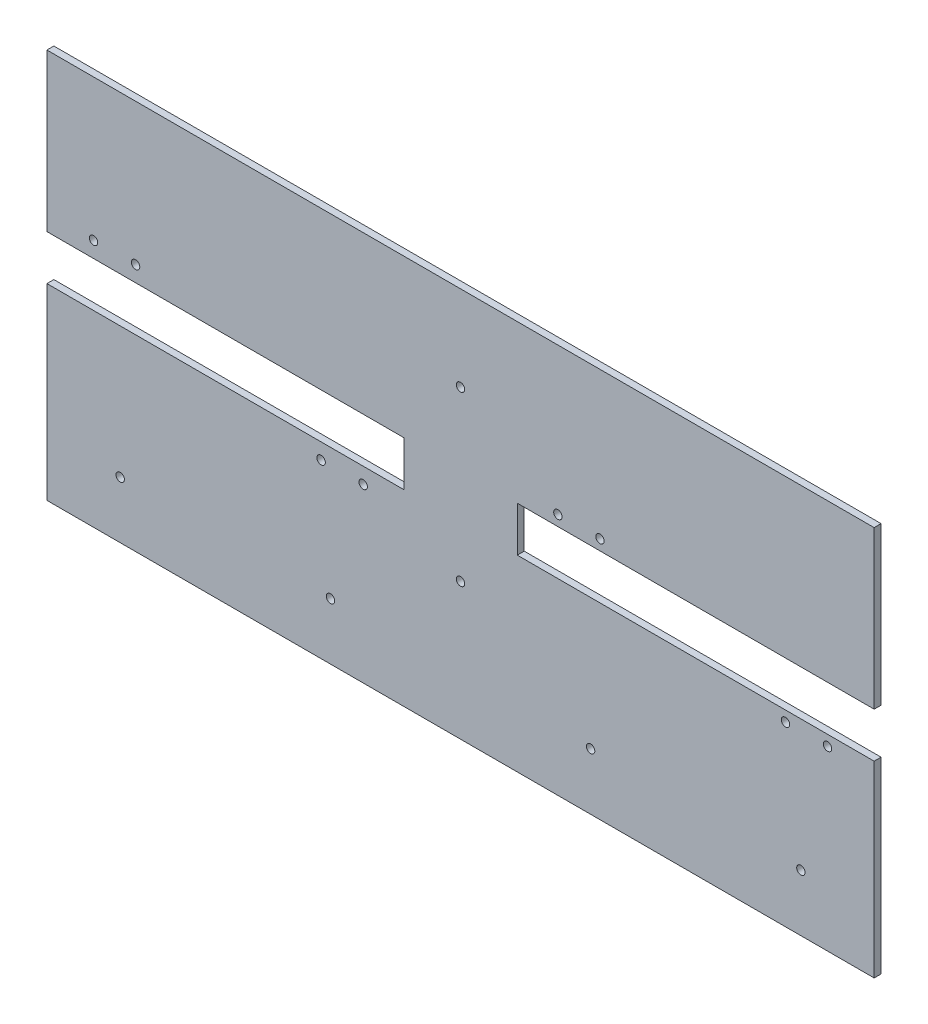
SolidWorks part; units mm, degrees
material "Balsa"
ref_plane "Front Plane" through (0, 0, 0) normal (0, 0, 1) x (1, 0, 0)
ref_plane "Top Plane" through (0, 0, 0) normal (0, 1, 0) x (1, 0, 0)
ref_plane "Right Plane" through (0, 0, 0) normal (1, 0, 0) x (0, 0, -1)
sketch "Sketch1" plane through (0, 0, 0) normal (0, 0, 1) x (1, 0, 0)
  line L0 (223.7, 160.9919) -> (54, 160.9919) construction
  line L1 (223.7, -24.5) -> (-169.7, -24.5)
  line L2 (223.7, -24.5) -> (223.7, 160.9919)
  line L3 (223.7, 160.9919) -> (-169.7, 160.9919)
  line L4 (-169.7, -24.5) -> (-169.7, 160.9919)
  line L5 (223.7, -24.5) -> (-169.7, 160.9919) construction
  line L6 (223.7, 160.9919) -> (-169.7, -24.5) construction
  line L7 (227, -24.5) -> (223.7, -24.5) construction
  line L10 (223.7, 144.1231) -> (223.7, -24.5) construction
  line L11 (-169.7, -24.5) -> (-169.7, 144.1269) construction
  point P4 (27, 68.246)
extrude "Boss-Extrude1" add sketch "Sketch1" along normal up to surface (3.3 mm away)
sketch "Sketch2" plane through (0, 0, 0) normal (0, 0, -1) x (-1, 0, 0)
  line L0 (-223.7, 160.9919) -> (169.7, 160.9919) construction
  line L1 (0, 0) -> (-54, 0)
  line L2 (0, 0) -> (0, 160.9919)
  line L3 (0, 160.9919) -> (-54, 160.9919)
  line L4 (-54, 0) -> (-54, 160.9919)
  line L5 (0, 0) -> (-54, 160.9919) construction
  line L6 (0, 160.9919) -> (-54, 0) construction
  line L7 (-54, 262.7) -> (-54, 0) construction
  line L8 (-27, 0) -> (-27, 160.9919) construction
  line L9 (169.7, 160.9919) -> (169.7, -24.5) construction
  line L10 (-223.7, 29.5) -> (-54, 29.5)
  line L11 (-223.7, 29.5) -> (-223.7, -24.5)
  line L12 (-223.7, -24.5) -> (-54, -24.5)
  line L13 (-54, 29.5) -> (-54, -24.5)
  line L14 (-223.7, 29.5) -> (-54, -24.5) construction
  line L15 (-223.7, -24.5) -> (-54, 29.5) construction
  line L16 (169.7, 29.5) -> (0, 29.5)
  line L17 (169.7, 29.5) -> (169.7, -24.5)
  line L18 (169.7, -24.5) -> (0, -24.5)
  line L19 (0, 29.5) -> (0, -24.5)
  line L20 (169.7, 29.5) -> (0, -24.5) construction
  line L21 (169.7, -24.5) -> (0, 29.5) construction
  line L22 (-223.7, 2.5) -> (169.7, 2.5) construction
  line L23 (-138.85, -24.5) -> (-138.85, 29.5) construction
  circle A0 centre (-27, 40.496) radius 2
  circle A1 centre (-27, 120.496) radius 2
  circle A2 centre (-188.85, 2.5) radius 2
  circle A3 centre (-88.85, 2.5) radius 2
  circle A4 centre (34.85, 2.5) radius 2
  circle A5 centre (134.85, 2.5) radius 2
  point P4 (-27, 80.496)
  point P20 (-138.85, 2.5)
  point P27 (84.85, 2.5)
  dimension "D1" = 4
  dimension "D2" = 4
  dimension "D3" = 40
  dimension "D4" = 40
  dimension "D5" = 4
  dimension "D6" = 50
extrude "Cut-Extrude1" cut sketch "Sketch2" against normal blind 4 contours A1 | A0 | A2 | A3 | A5 | A4
sketch "Sketch3" plane through (0, 0, 0) normal (0, 0, -1) x (-1, 0, 0)
  line L0 (169.7, 160.9919) -> (169.7, -24.5) construction
  line L1 (169.7, 64.8) -> (-223.7, 64.8)
  line L2 (169.7, 64.8) -> (169.7, 86.2)
  line L3 (169.7, 86.2) -> (-223.7, 86.2)
  line L4 (-223.7, 64.8) -> (-223.7, 86.2)
  line L5 (169.7, 64.8) -> (-223.7, 86.2) construction
  line L6 (169.7, 86.2) -> (-223.7, 64.8) construction
  line L7 (-223.7, -24.5) -> (-223.7, 160.9919) construction
  line L8 (35.8344, 64.8) -> (9.0983, 64.8) construction
  line L9 (142.922, 86.2) -> (163.7817, 86.2) construction
  line L10 (0, 64.8) -> (0, 86.2)
  line L11 (-54, 64.8) -> (-54, 86.2)
  line L12 (-54, 262.7) -> (-54, 0) construction
  line L13 (0, 262.7) -> (0, 0) construction
  line L14 (0, 262.7) -> (0, 0) construction
  point P4 (-27, 75.5)
  line M7 (-223.7, 160.9919) -> (-223.7, -24.5)
  line M9 (169.7, -24.5) -> (169.7, 160.9919)
extrude "Cut-Extrude2" cut sketch "Sketch3" against normal blind 6 contours L10 L1 L3 M9 | L1 L11 L3 M7
sketch "Sketch4" plane through (0, 0, 3.3) normal (0, 0, 1) x (1, 0, 0)
  circle A0 centre (93.3034, 91.2) radius 2
  circle A1 centre (73.3034, 91.2) radius 2
  circle A2 centre (181.5258, 59.8) radius 2
  circle A3 centre (201.5258, 59.8) radius 2
  circle A4 centre (-127.5258, 93.7) radius 2
  circle A5 centre (-147.5258, 93.7) radius 2
  circle A6 centre (-19.3034, 57.3) radius 2
  circle A7 centre (-39.3034, 57.3) radius 2
  circle A8 centre (-39.3034, 57.3) radius 2 construction
  circle A9 centre (-19.3034, 57.3) radius 2 construction
  circle A10 centre (-127.5258, 93.7) radius 2 construction
  circle A11 centre (-147.5258, 93.7) radius 2 construction
  circle A12 centre (181.5258, 59.8) radius 2 construction
  circle A13 centre (93.3034, 91.2) radius 2 construction
  circle A14 centre (73.3034, 91.2) radius 2 construction
  circle A15 centre (201.5258, 59.8) radius 2 construction
extrude "Cut-Extrude3" cut sketch "Sketch4" against normal through all
